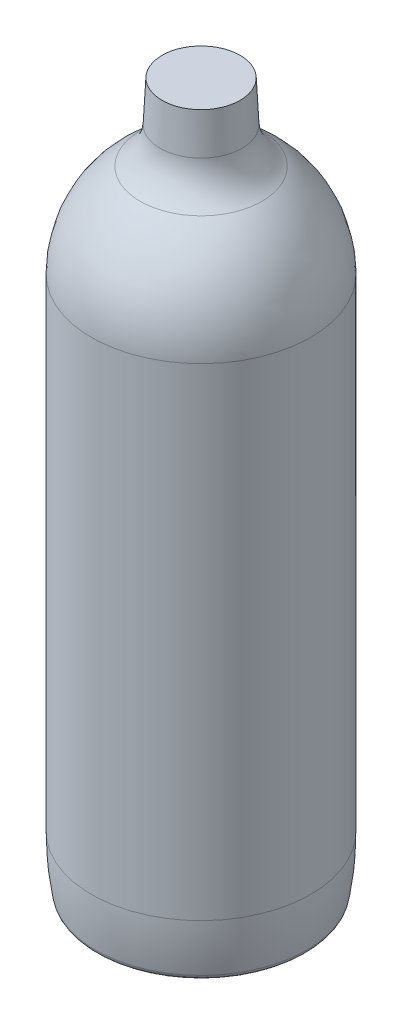
SolidWorks part; units mm, degrees
ref_plane "Přední rovina" through (0, 0, 0) normal (0, 0, 1) x (1, 0, 0)
ref_plane "Horní rovina" through (0, 0, 0) normal (0, 1, 0) x (1, 0, 0)
ref_plane "Pravá rovina" through (0, 0, 0) normal (1, 0, 0) x (0, 0, -1)
sketch "Skica1" plane through (0, 0, 0) normal (0, 0, 1) x (1, 0, 0)
  line L0 (0, 0) -> (0, 289) construction
  line L1 (-2, 9.9374) -> (0, 9.9374)
  line L2 (0, 231) -> (0, 9.9374)
  line L3 (0, 8) -> (-3.8605, 8) construction
  line L4 (0, 0) -> (-46.7512, 0) construction
  line L6 (-9.0428, 8.6957) -> (-31.4948, 2.0815)
  line L7 (-35.45, 176) -> (-35.45, 20)
  line L8 (-12.6188, 231) -> (0, 231)
  line L10 (0, 289) -> (-15.9004, 289) construction
  arc A6 (-9.0428, 8.6957) -> (-2, 9.9374) centre (0, -22) cw
  arc A7 (-34.03, 3.6551) -> (-31.4948, 2.0815) centre (-32.0599, 4) ccw
  arc A8 (-35.45, 20) -> (-34.03, 3.6551) centre (59.3268, 20) ccw
  arc A9 (-35.45, 176) -> (-19.7219, 206.2739) centre (1.55, 176) cw
  arc A10 (-19.7219, 206.2739) -> (-13.2534, 217.8833) centre (-28.5054, 218.7746) ccw
  arc A11 (-13.2534, 217.8833) -> (-12.6188, 231) centre (-667.0714, 256.0893) ccw
  dimension "D22" = 289
  dimension "D5" = 8
  dimension "D14" = 58
revolve "Rotovat1" add sketch "Skica1" angle 360 about L0
